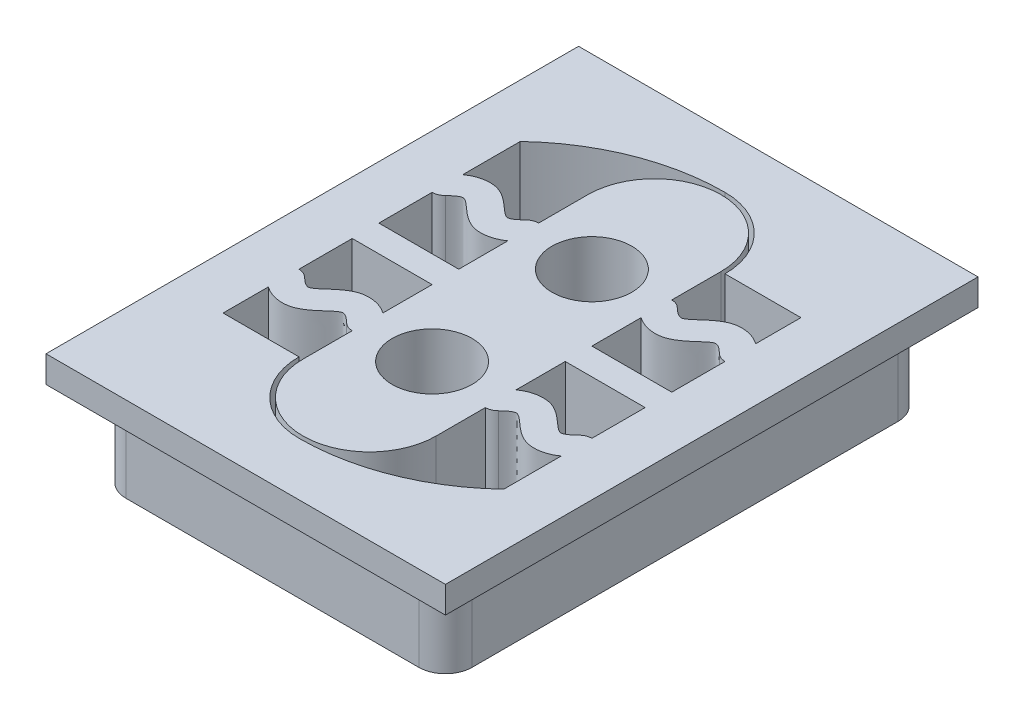
SolidWorks part; units mm, degrees
ref_plane "Front Plane" through (0, 0, 0) normal (0, 0, 1) x (1, 0, 0)
ref_plane "Top Plane" through (0, 0, 0) normal (0, 1, 0) x (1, 0, 0)
ref_plane "Right Plane" through (0, 0, 0) normal (1, 0, 0) x (0, 0, -1)
sketch "Sketch1" plane through (0, 0, 0) normal (0, 1, 0) x (1, 0, 0)
  line L1 (-6.5, -9) -> (6.5, -9)
  line L2 (-6.5, -9) -> (-6.5, 9)
  line L3 (-6.5, 9) -> (6.5, 9)
  line L4 (6.5, -9) -> (6.5, 9)
  line L5 (-6.5, -9) -> (6.5, 9) construction
  line L6 (-6.5, 9) -> (6.5, -9) construction
  point P0 (0, 0)
  dimension "D1" = 18
  dimension "D2" = 13
extrude "Boss-Extrude1" add sketch "Sketch1" along normal blind 3.2
sketch "Sketch2" plane through (0, 3.2, 0) normal (0, 1, 0) x (1, 0, 0)
  line L8 (7.5, -10) -> (7.5, 10)
  line L9 (7.5, 10) -> (-7.5, 10)
  line L10 (-7.5, 10) -> (-7.5, -10)
  line L11 (-7.5, -10) -> (7.5, -10)
  line L12 (7.5, -10) -> (7.5, 10)
  line L13 (7.5, 10) -> (-7.5, 10)
  line L14 (-7.5, 10) -> (-7.5, -10)
  line L15 (-7.5, -10) -> (7.5, -10)
  dimension "D1" = 1
extrude "Boss-Extrude2" add sketch "Sketch2" along normal blind 1
sketch "Sketch4" plane through (0, 0, 0) normal (0, -1, 0) x (1, 0, 0)
  line L4 (0, -3) -> (0, 3)
  line L5 (-2.65, 5.35) -> (-5.5, 5.35)
  line L6 (2.5, -5.35) -> (-2.5, -5.35)
  line L7 (2.5, -5.35) -> (2.5, 5.35)
  line L8 (5.5, -8) -> (5.5, 8)
  line L9 (5.5, 8) -> (-5.5, 8)
  line L10 (-5.5, 8) -> (-5.5, -8)
  line L11 (-5.5, -8) -> (5.5, -8)
  line L12 (5.5, -8) -> (5.5, 8)
  line L13 (5.5, 8) -> (-5.5, 8)
  line L14 (-5.5, 8) -> (-5.5, -8)
  line L15 (-5.5, -8) -> (5.5, -8)
  line L16 (2.5, 5.35) -> (-2.5, 5.35)
  line L17 (-2.5, -5.35) -> (-2.5, 5.35)
  line L18 (2.5, -5.35) -> (-2.5, 5.35) construction
  line L19 (2.5, 5.35) -> (-2.5, -5.35) construction
  line L20 (2.65, -5.35) -> (5.5, -5.35)
  line L21 (-4.2, 8) -> (-4.2, -8) construction
  line L22 (-3.8, -8) -> (-3.8, 8) construction
  line L23 (-5.5, 3) -> (-2.5, 3) construction
  line L24 (-4.2, 3.1728) -> (-4.2, 3) construction
  line L25 (-3.8, 2.8272) -> (-3.8, 3) construction
  line L26 (-4.2, 3.1728) -> (-4.2, 3)
  line L27 (-3.8, 3) -> (-3.8, 2.8272)
  line L28 (-2.5, 0) -> (-5.5, 0)
  line L29 (2.5, 0) -> (5.5, 0)
  line L30 (-2.5, 0.5) -> (-5.5, 0.5)
  line L31 (2.5, -0.5) -> (5.5, -0.5)
  line L32 (-2.5, -0.5) -> (-5.5, -0.5)
  line L33 (2.5, 0.5) -> (5.5, 0.5)
  circle A0 centre (0, 3) radius 1.5
  circle A1 centre (0, -3) radius 1.5
  arc A2 (-2.5, 5.35) -> (2.5, 5.35) centre (0, 5.35) cw
  arc A3 (-2.5, -5.35) -> (2.5, -5.35) centre (0, -5.35) ccw
  arc A4 (0, 8) -> (-2.65, 5.35) centre (0, 5.35) ccw
  arc A5 (0, 8) -> (5.5, 5.8095) centre (0, 0) cw
  arc A6 (0, -8) -> (2.65, -5.35) centre (0, -5.35) ccw
  arc A7 (0, -8) -> (-5.5, -5.8095) centre (0, 0) cw
  arc A8 (-5.1475, 2.6454) -> (-5.8525, 3.3546) centre (-5.5, 3) cw
  arc A9 (-2.1475, 2.6454) -> (-2.8525, 3.3546) centre (-2.5, 3) ccw
  arc A10 (5.8525, 3.3546) -> (5.1475, 2.6454) centre (5.5, 3) cw
  arc A11 (2.8525, 3.3546) -> (2.1475, 2.6454) centre (2.5, 3) ccw
  arc A12 (5.1475, -2.6454) -> (5.8525, -3.3546) centre (5.5, -3) cw
  arc A13 (2.1475, -2.6454) -> (2.8525, -3.3546) centre (2.5, -3) ccw
  arc A14 (-5.8525, -3.3546) -> (-5.1475, -2.6454) centre (-5.5, -3) cw
  arc A15 (-2.8525, -3.3546) -> (-2.1475, -2.6454) centre (-2.5, -3) ccw
  arc A16 (-2.5, 0.5) -> (-2.5, -0.5) centre (-2.5, 0) cw
  arc A17 (-5.5, 0.5) -> (-5.5, -0.5) centre (-5.5, 0) ccw
  arc A18 (2.5, -0.5) -> (2.5, 0.5) centre (2.5, 0) cw
  arc A19 (5.5, -0.5) -> (5.5, 0.5) centre (5.5, 0) ccw
  spline S0 degree 3 poles (-5.5, 3) (-4.0778, 4.4136) (-3.9222, 1.5864) (-2.5, 3) knots 0 0 0 0 1 1 1 1
  spline S1 degree 3 poles (5.5, 3) (4.0778, 4.4136) (3.9222, 1.5864) (2.5, 3) knots 0 0 0 0 1 1 1 1
  spline S2 degree 3 poles (5.5, -3) (4.0778, -4.4136) (3.9222, -1.5864) (2.5, -3) knots 0 0 0 0 1 1 1 1
  spline S3 degree 3 poles (-5.5, -3) (-4.0778, -4.4136) (-3.9222, -1.5864) (-2.5, -3) knots 0 0 0 0 1 1 1 1
  spline S4 degree 1 poles (-5.1475, 2.6454) (-2.1475, 2.6454) knots 0 0 1 1 construction
  spline S5 degree 3 poles (-5.1475, 2.6454) (-5.0875, 2.7051) (-4.9388, 2.8332) (-4.8159, 2.8957) (-4.7521, 2.9097) (-4.7197, 2.9084) (-4.6067, 2.8672) (-4.3449, 2.64) (-4.0157, 2.3383) (-3.4967, 2.0501) (-2.883, 2.1138) (-2.462, 2.3606) (-2.245, 2.5485) (-2.1475, 2.6454) knots 0 0 0 0 0.0625 0.125 0.1875 0.25 0.375 0.5 0.625 0.75 0.875 0.9375 1 1 1 1
  spline S6 degree 1 poles (-5.8525, 3.3546) (-2.8525, 3.3546) knots 0 0 1 1 construction
  spline S7 degree 3 poles (-5.8525, 3.3546) (-5.755, 3.4515) (-5.538, 3.6394) (-5.117, 3.8862) (-4.5033, 3.9499) (-3.9843, 3.6617) (-3.6551, 3.36) (-3.3933, 3.1328) (-3.2803, 3.0916) (-3.2479, 3.0903) (-3.1841, 3.1043) (-3.0612, 3.1668) (-2.9125, 3.2949) (-2.8525, 3.3546) knots 0 0 0 0 0.0625 0.125 0.25 0.375 0.5 0.625 0.75 0.8125 0.875 0.9375 1 1 1 1
  spline S8 degree 1 poles (5.8525, 3.3546) (2.8525, 3.3546) knots 0 0 1 1 construction
  spline S9 degree 3 poles (5.8525, 3.3546) (5.755, 3.4515) (5.538, 3.6394) (5.117, 3.8862) (4.5033, 3.9499) (3.9843, 3.6617) (3.6551, 3.36) (3.3933, 3.1328) (3.2803, 3.0916) (3.2479, 3.0903) (3.1841, 3.1043) (3.0612, 3.1668) (2.9125, 3.2949) (2.8525, 3.3546) knots 0 0 0 0 0.0625 0.125 0.25 0.375 0.5 0.625 0.75 0.8125 0.875 0.9375 1 1 1 1
  spline S10 degree 1 poles (5.1475, -2.6454) (2.1475, -2.6454) knots 0 0 1 1 construction
  spline S11 degree 3 poles (5.1475, -2.6454) (5.0875, -2.7051) (4.9388, -2.8332) (4.8159, -2.8957) (4.7521, -2.9097) (4.7197, -2.9084) (4.6067, -2.8672) (4.3449, -2.64) (4.0157, -2.3383) (3.4967, -2.0501) (2.883, -2.1138) (2.462, -2.3606) (2.245, -2.5485) (2.1475, -2.6454) knots 0 0 0 0 0.0625 0.125 0.1875 0.25 0.375 0.5 0.625 0.75 0.875 0.9375 1 1 1 1
  spline S12 degree 1 poles (-5.8525, -3.3546) (-2.8525, -3.3546) knots 0 0 1 1 construction
  spline S13 degree 3 poles (-5.8525, -3.3546) (-5.755, -3.4515) (-5.538, -3.6394) (-5.117, -3.8862) (-4.5033, -3.9499) (-3.9843, -3.6617) (-3.6551, -3.36) (-3.3933, -3.1328) (-3.2803, -3.0916) (-3.2479, -3.0903) (-3.1841, -3.1043) (-3.0612, -3.1668) (-2.9125, -3.2949) (-2.8525, -3.3546) knots 0 0 0 0 0.0625 0.125 0.25 0.375 0.5 0.625 0.75 0.8125 0.875 0.9375 1 1 1 1
  spline S14 degree 1 poles (5.1475, 2.6454) (2.1475, 2.6454) knots 0 0 1 1 construction
  spline S15 degree 3 poles (5.1475, 2.6454) (5.0875, 2.7051) (4.9388, 2.8332) (4.8159, 2.8957) (4.7521, 2.9097) (4.7197, 2.9084) (4.6067, 2.8672) (4.3449, 2.64) (4.0157, 2.3383) (3.4967, 2.0501) (2.883, 2.1138) (2.462, 2.3606) (2.245, 2.5485) (2.1475, 2.6454) knots 0 0 0 0 0.0625 0.125 0.1875 0.25 0.375 0.5 0.625 0.75 0.875 0.9375 1 1 1 1
  spline S16 degree 1 poles (5.8525, -3.3546) (2.8525, -3.3546) knots 0 0 1 1 construction
  spline S17 degree 3 poles (5.8525, -3.3546) (5.755, -3.4515) (5.538, -3.6394) (5.117, -3.8862) (4.5033, -3.9499) (3.9843, -3.6617) (3.6551, -3.36) (3.3933, -3.1328) (3.2803, -3.0916) (3.2479, -3.0903) (3.1841, -3.1043) (3.0612, -3.1668) (2.9125, -3.2949) (2.8525, -3.3546) knots 0 0 0 0 0.0625 0.125 0.25 0.375 0.5 0.625 0.75 0.8125 0.875 0.9375 1 1 1 1
  spline S18 degree 1 poles (-5.1475, -2.6454) (-2.1475, -2.6454) knots 0 0 1 1 construction
  spline S19 degree 3 poles (-5.1475, -2.6454) (-5.0875, -2.7051) (-4.9388, -2.8332) (-4.8159, -2.8957) (-4.7521, -2.9097) (-4.7197, -2.9084) (-4.6067, -2.8672) (-4.3449, -2.64) (-4.0157, -2.3383) (-3.4967, -2.0501) (-2.883, -2.1138) (-2.462, -2.3606) (-2.245, -2.5485) (-2.1475, -2.6454) knots 0 0 0 0 0.0625 0.125 0.1875 0.25 0.375 0.5 0.625 0.75 0.875 0.9375 1 1 1 1
  point P3 (0, 0)
  point P5 (0, 0)
  dimension "D3" = 3
  dimension "D6" = 1.3
  dimension "D8" = 3.5
  dimension "D2" = 6
  dimension "D4" = 10.7
  dimension "D5" = 5
  dimension "D7" = 1.3
  dimension "D9" = 0.5
  dimension "D1" = 1
  dimension "D10" = 0.5
  dimension "D11" = 0.5
  dimension "D12" = 0.5
extrude "Cut-Extrude2" cut sketch "Sketch4" against normal blind 10
fillet "Fillet1" radius 1 4 edges at (6.5, 1.6, 9) (6.5, 1.6, -9) (-6.5, 1.6, -9) (-6.5, 1.6, 9)
mirror "Mirror1" [suppressed]
delete or keep bodies "Body-Delete/Keep 1" [suppressed] type keep bodies bodies 104
